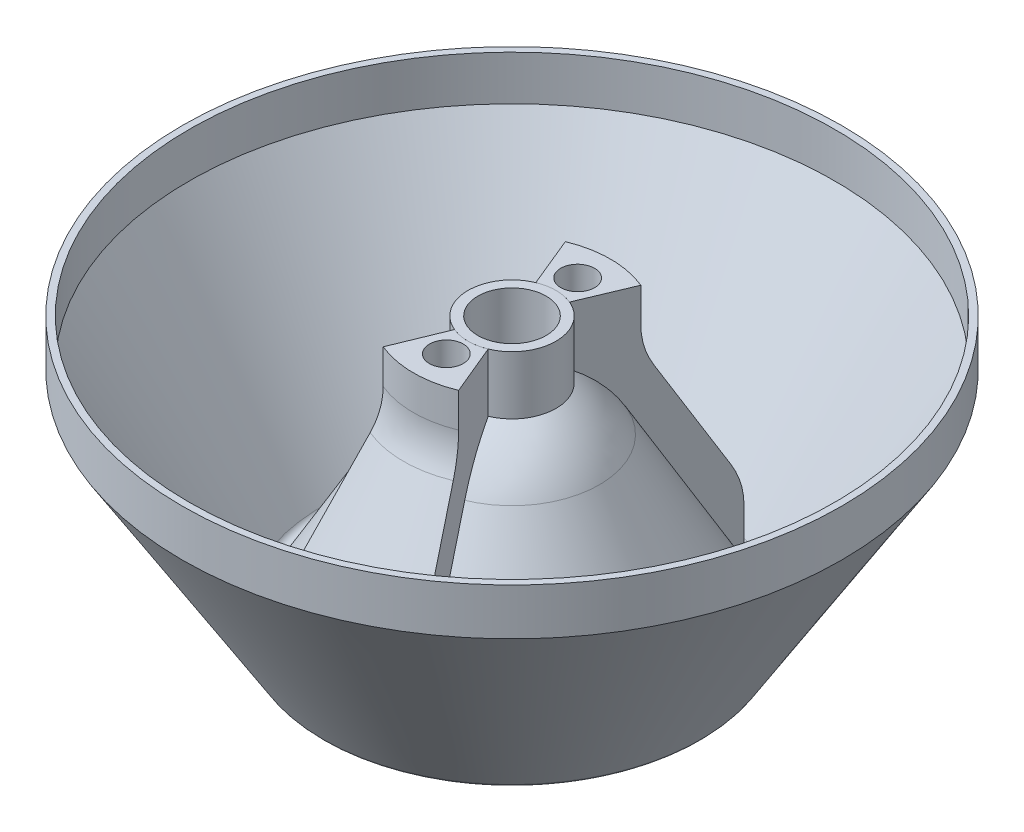
SolidWorks part; units mm, degrees
ref_plane "Front Plane" through (0, 0, 0) normal (0, 0, 1) x (1, 0, 0)
ref_plane "Top Plane" through (0, 0, 0) normal (0, 1, 0) x (1, 0, 0)
ref_plane "Right Plane" through (0, 0, 0) normal (1, 0, 0) x (0, 0, -1)
sketch "Sketch1" plane through (0, 0, 0) normal (1, 0, 0) x (0, 0, -1)
  line L0 (-48.729, 20.833) -> (-48.729, 13.9354)
  line L5 (-48.729, 20.833) -> (48.729, 20.833) construction
  line L6 (-48.729, 20.833) -> (-48.729, -20.833) construction
  line L7 (-48.729, -20.833) -> (48.729, -20.833) construction
  line L8 (48.729, 20.833) -> (48.729, -20.833) construction
  line L9 (-48.729, 20.833) -> (48.729, -20.833) construction
  line L10 (-48.729, -20.833) -> (48.729, 20.833) construction
  line L11 (-48.729, 13.9354) -> (-27.9212, -19.4195)
  line L12 (-47.729, 20.833) -> (-47.729, 14.2217)
  line L13 (-47.729, 14.2217) -> (-27.9545, -17.4768)
  line L14 (-26.24, -17.4475) -> (-12.9089, 5.6485)
  line L15 (-26.2067, -19.3902) -> (-12.0428, 5.1486)
  line L16 (-47.729, 14.2217) -> (-27.0728, -18.8903) construction
  line L17 (-27.0728, -18.8903) -> (-12.9089, 5.6485) construction
  line L18 (-47.729, 20.833) -> (-48.729, 20.833)
  line L19 (0, 0) -> (0, -20.833) construction
  line L24 (-6.5023, 20.833) -> (-6.5023, 12.2224)
  line L29 (-5.0525, 20.833) -> (-6.5023, 20.833)
  line L30 (-5.0525, 20.833) -> (-5.0525, 11.8994)
  arc A0 (-27.9212, -19.4195) -> (-26.2067, -19.3902) centre (-27.0728, -18.8903) ccw
  arc A1 (-12.0428, 5.1486) -> (-5.0525, 11.8994) centre (3.2196, -3.6609) cw
  arc A2 (-12.9089, 5.6485) -> (-0.1361, 14.6567) centre (3.2196, -3.6609) cw construction
  arc A3 (-12.9089, 5.6485) -> (-6.5023, 12.2224) centre (3.2196, -3.6609) cw
  arc A4 (-27.9545, -17.4768) -> (-26.24, -17.4475) centre (-27.1061, -16.9476) ccw
  arc A5 (-27.0728, -18.8903) -> (-27.0728, -18.8903) centre (-27.0728, -18.8903) ccw construction
  arc A6 (-12.0428, 5.1486) -> (0.0441, 13.6731) centre (3.2196, -3.6609) cw construction
  point P0 (0, 0)
  point P14 (-27.0395, -20.833)
  dimension "D1" = 1
  dimension "D3" = 1
  dimension "D2" = 1
revolve "Revolve7" add sketch "Sketch1" angle 360 about L19
sketch "Sketch4" plane through (0, 0, 0) normal (1, 0, 0) x (0, 0, -1)
  line L2 (-26.24, -17.4475) -> (-26.24, -10.3923)
  line L5 (0, 0) -> (0, -20.833) construction
  line L7 (-30.5704, -14.9479) -> (-17.2393, 8.1481)
  line L8 (-24.7669, -4.8934) -> (-16.0437, 10.2195)
  line L9 (-14.5706, 15.7184) -> (-14.5706, 20.8073)
  line L10 (-14.5706, 20.8073) -> (-6.5023, 20.833)
  line L11 (-26.24, -17.4475) -> (-12.9089, 5.6485)
  line L12 (-26.24, -17.4475) -> (-12.9089, 5.6485)
  line L13 (-6.5023, 20.833) -> (-6.5023, 12.2224)
  arc A2 (-24.7669, -4.8934) -> (-26.24, -10.3923) centre (-15.24, -10.3923) ccw
  arc A5 (-9.1126, 16.4869) -> (-17.2393, 8.1481) centre (3.2196, -3.6609) ccw
  arc A8 (-14.5706, 15.7184) -> (-16.0437, 10.2195) centre (-25.5706, 15.7184) cw
  arc A10 (-6.5023, 12.2224) -> (-12.9089, 5.6485) centre (3.2196, -3.6609) ccw
  arc A11 (-6.5023, 12.2224) -> (-12.9089, 5.6485) centre (3.2196, -3.6609) ccw
  dimension "D2" = 11
  dimension "D3" = 5
  dimension "D1" = 11
  dimension "D4" = 0
  dimension "D5" = 0
revolve "Revolve9" add sketch "Sketch4" angle 45 mid plane about L5
sketch "Sketch6" plane through (0, 0, 0) normal (1, 0, 0) x (0, 0, -1)
  line L139 (-23.9008, -5.3933) -> (-15.1776, 9.7196)
  line L140 (-23.9008, -5.3933) -> (-15.1776, 9.7196)
  line L142 (-25.24, -17.4475) -> (-25.24, -10.3923)
  line L143 (-25.24, -13.7146) -> (-25.24, -10.3923)
  line L144 (-7.0244, 13.0753) -> (-13.8653, 13.0753)
  line L145 (-27.1061, -16.9476) -> (-13.775, 6.1484)
  line L146 (-25.24, -13.7146) -> (-13.775, 6.1484)
  arc A80 (-23.9008, -5.3933) -> (-25.24, -10.3923) centre (-15.24, -10.3923) ccw
  arc A81 (-23.9008, -5.3933) -> (-25.24, -10.3923) centre (-15.24, -10.3923) ccw
  arc A83 (-7.0244, 13.0753) -> (-13.775, 6.1484) centre (3.2196, -3.6609) ccw
  arc A84 (-7.0244, 13.0753) -> (-13.775, 6.1484) centre (3.2196, -3.6609) ccw
  arc A86 (-15.1776, 9.7196) -> (-13.5706, 15.7184) centre (-25.5706, 15.7184) ccw
  arc A87 (-15.1776, 9.7196) -> (-13.8653, 13.0753) centre (-25.5706, 15.7184) ccw
  dimension "D1" = 1
  dimension "D2" = 1
  dimension "D3" = 1
  dimension "D4" = 1
  dimension "D5" = 1
  dimension "D6" = 1
revolve "Cut-Revolve4" cut sketch "Sketch6" angle 30 mid plane about L19
sketch "Sketch11" plane through (0, 13.0753, 0) normal (0, -1, 0) x (1, 0, 0)
  line L0 (0, 6.5023) -> (0, 12.9089) construction
  circle A0 centre (0, 9.7056) radius 2.5
extrude "Cut-Extrude1" cut sketch "Sketch11" against normal up to next
pattern_circular "CirPattern12" count 2 over 180 about axis through (0, 0, 0) along (0, 1, 0) of bodies 109 106
